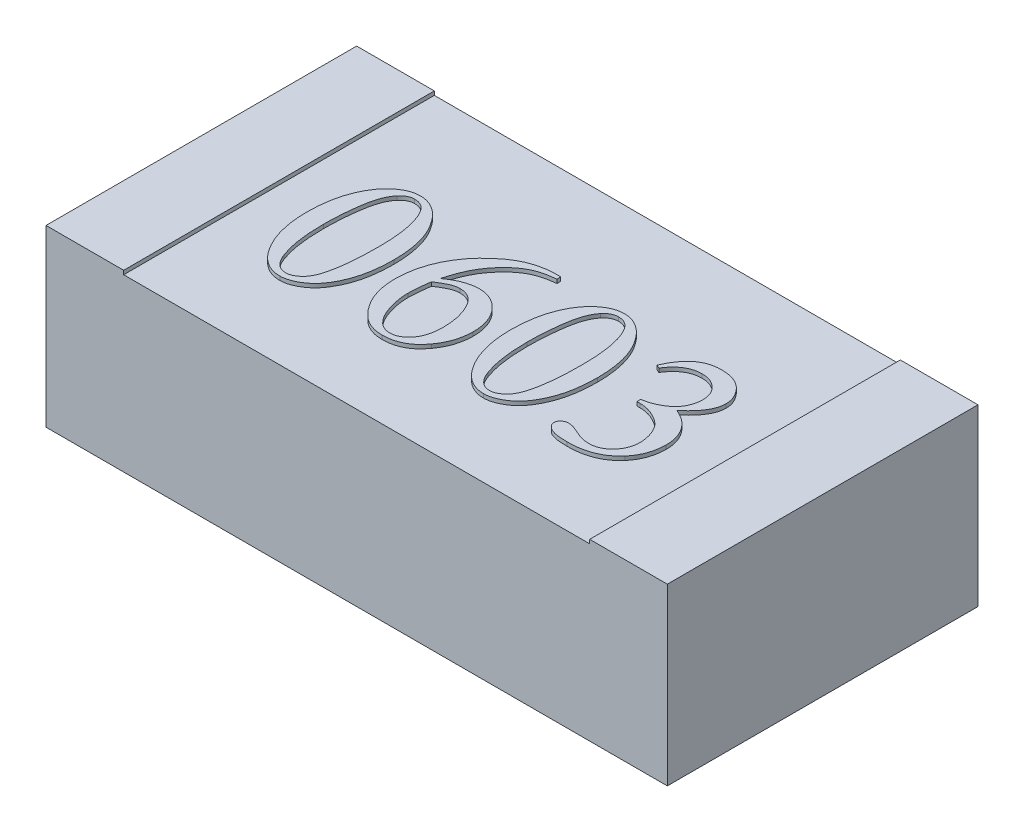
SolidWorks part; units mm, degrees
material "45"
ref_plane "前视基准面" through (0, 0, 0) normal (0, 0, 1) x (1, 0, 0)
ref_plane "上视基准面" through (0, 0, 0) normal (0, 1, 0) x (1, 0, 0)
ref_plane "右视基准面" through (0, 0, 0) normal (1, 0, 0) x (0, 0, -1)
sketch "草图1" plane through (0, 0, 0) normal (0, 1, 0) x (1, 0, 0)
  line L1 (-0.8, 0.4) -> (0.8, 0.4)
  line L2 (-0.8, 0.4) -> (-0.8, -0.4)
  line L3 (-0.8, -0.4) -> (0.8, -0.4)
  line L4 (0.8, 0.4) -> (0.8, -0.4)
  line L5 (-0.8, 0.4) -> (0.8, -0.4) construction
  line L6 (-0.8, -0.4) -> (0.8, 0.4) construction
  point P0 (0, 0)
  dimension "D1" = 1.6
  dimension "D2" = 0.8
extrude "凸台-拉伸1" add sketch "草图1" along normal blind 0.45
sketch "草图2" plane through (0, 0.45, 0) normal (0, 1, 0) x (1, 0, 0)
  line L0 (0.8, 0.4) -> (-0.8, 0.4) construction
  line L1 (0.6, -0.4) -> (-0.6, -0.4)
  line L2 (0.6, -0.4) -> (0.6, 0.4)
  line L3 (0.6, 0.4) -> (-0.6, 0.4)
  line L4 (-0.6, -0.4) -> (-0.6, 0.4)
  line L5 (0.6, -0.4) -> (-0.6, 0.4) construction
  line L6 (0.6, 0.4) -> (-0.6, -0.4) construction
  point P0 (0, 0)
  dimension "D1" = 1.2
extrude "切除-拉伸1" cut sketch "草图2" against normal blind 0.01
sketch "草图3" plane through (0, 0.44, 0) normal (0, 1, 0) x (1, 0, 0)
  line L0 (-0.5135, -0.2069) -> (0.5514, -0.2069) construction
  text T0 "0603" font "Times New Roman" height 0.35
extrude "凸台-拉伸2" add sketch "草图3" along normal blind 0.01
